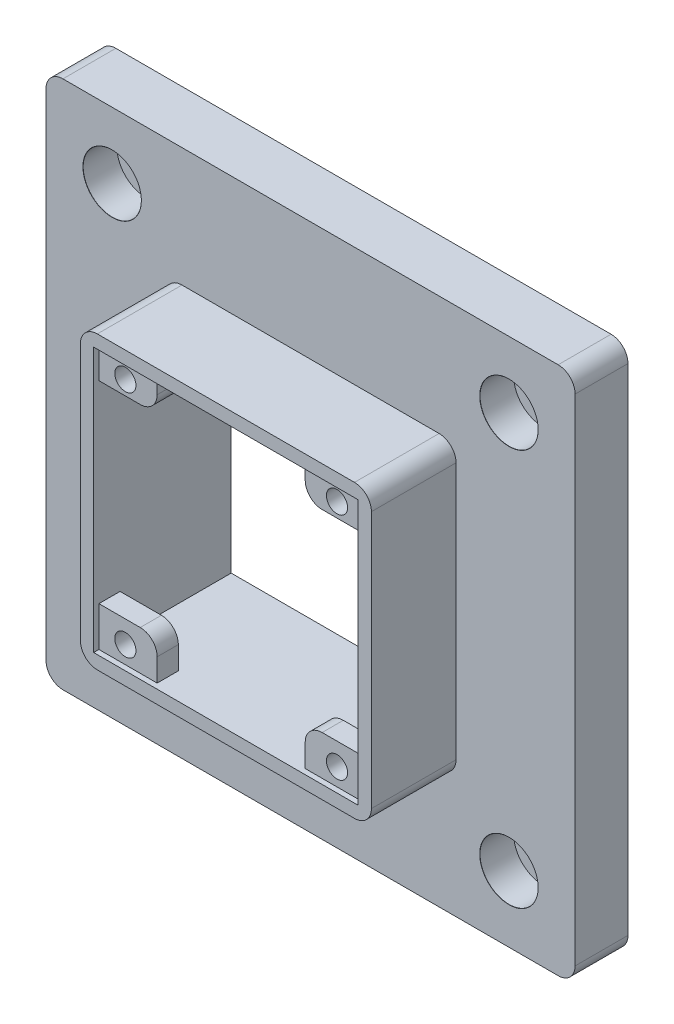
SolidWorks part; units mm, degrees
ref_plane "Front Plane" through (0, 0, 0) normal (1, 0, 0) x (0, 1, 0)
ref_plane "Top Plane" through (0, 0, 0) normal (0, 0, 1) x (0, 1, 0)
ref_plane "Right Plane" through (0, 0, 0) normal (0, 1, 0) x (-1, 0, 0)
sketch "Sketch2" plane through (0, 0, 0) normal (0, 0, 1) x (0, 1, 0)
  line L0 (25, 25) -> (50, 50)
  line L1 (-50, 50) -> (50, 50)
  line L2 (-50, 50) -> (-50, -50)
  line L3 (-50, -50) -> (50, -50)
  line L4 (50, 50) -> (50, -50)
  line L5 (-50, 50) -> (50, -50) construction
  line L6 (-50, -50) -> (50, 50) construction
  line L7 (-25, -25) -> (25, -25)
  line L8 (-25, -25) -> (-25, 25)
  line L9 (-25, 25) -> (25, 25)
  line L10 (25, -25) -> (25, 25)
  line L11 (-25, -25) -> (25, 25) construction
  line L12 (-25, 25) -> (25, -25) construction
  line L13 (25, -25) -> (50, -50)
  line L14 (37.5, 37.5) -> (37.5, -37.5)
  line L15 (37.5, -37.5) -> (37.5, -50)
  point P0 (0, 0)
  point P6 (0, 0)
  dimension "D1" = 50
  dimension "D2" = 100
extrude "Boss-Extrude1" add sketch "Sketch2" along normal blind 10 contours L7 L10 L9 L8 | L2 L1 L4 L3
sketch "Sketch5" plane through (0, 0, 10) normal (0, 0, 1) x (1, 0, 0)
  line L0 (-37.5, 37.5) -> (37.5, 37.5)
  line L2 (5.5, 0) -> (-5.5, 0) construction
  point P0 (-37.5, 37.5)
  point P1 (37.5, 37.5)
  point P13 (37.5, -37.5)
  point P14 (-37.5, -37.5)
hole_wizard "CBORE for M6 Hex Socket Head Cap Screw1" positions "Sketch5" profile "Sketch6" counterbore size "M6" standard "ISO" end condition through all
sketch "Sketch6" plane through (-37.5, 37.5, 10) normal (1, 0, 0) x (0, -1, 0)
  line L0 (0, 0) -> (0, 10)
  line L1 (0, 10) -> (3.3, 10)
  line L3 (3.3, 10) -> (3.3, 6.4)
  line L4 (5.5, 6.4) -> (3.3, 6.4)
  line L5 (5.5, 6.4) -> (5.5, 0.025)
  line L6 (5.5, 0.025) -> (5.525, 0)
  line L7 (5.525, 0) -> (0, 0)
  line L8 (-5.5, 0.025) -> (-5.525, 0) construction
  line L11 (0, -6.35) -> (0, 107.95) construction
  dimension "Thru Hole Dia." = 6.6
  dimension "Thru Hole Depth" = 10
  dimension "C'Bore Dia." = 11
  dimension "C'Bore Depth" = 6.4
  dimension "Near C'Sink Dia." = 11.05
  dimension "Near C'Sink Angle" = 90
sketch "Sketch7" plane through (0, 0, 10) normal (0, 0, 1) x (1, 0, 0)
  line L0 (25, 25) -> (50, 50) construction
  line L1 (-27.5, -27.5) -> (27.5, -27.5)
  line L2 (-27.5, -27.5) -> (-27.5, 27.5)
  line L3 (-27.5, 27.5) -> (27.5, 27.5)
  line L4 (27.5, -27.5) -> (27.5, 27.5)
  line L5 (-27.5, -27.5) -> (27.5, 27.5) construction
  line L6 (-27.5, 27.5) -> (27.5, -27.5) construction
  point P0 (0, 0)
  line M13 (25, 25) -> (25, -25)
  line M14 (25, -25) -> (-25, -25)
  line M15 (-25, -25) -> (-25, 25)
  line M16 (-25, 25) -> (25, 25)
  dimension "D1" = 55
extrude "Boss-Extrude2" add sketch "Sketch7" along normal blind 16 contours L1 L4 L3 L2 M16 M13 M14 M15
sketch "Sketch8" plane through (0, 0, 26) normal (0, 0, 1) x (1, 0, 0)
  line L0 (-50, -50) -> (50, 50) construction
  line L5 (-24.7015, -24.7015) -> (24.7015, 24.7015) construction
  line L7 (25, -25) -> (25, 25) construction
  line L8 (-25, 25) -> (25, 25)
  line L9 (-25, 25) -> (-25, 19)
  line L10 (-25, 19) -> (-13.9912, 19)
  line L11 (25, 25) -> (25, 19)
  line L12 (-13.9912, -17.5) -> (-25, -17.5)
  line L13 (-25, 25) -> (-13.9912, 25)
  line L14 (-25, -25) -> (25, -25)
  line L15 (-25, -25) -> (-25, -15)
  line L17 (25, -25) -> (25, -15)
  line L18 (-19.721, 19.721) -> (24.7015, -24.7015) construction
  line L19 (13.9912, 19) -> (25, 19)
  line L20 (-13.9912, -25) -> (-13.9912, -17.5)
  line L21 (13.9912, -25) -> (-13.9912, -25)
  line L22 (13.9912, -25) -> (13.9912, -17.5)
  line L24 (0, -25) -> (0, -24.7015)
  line L27 (13.9912, 19) -> (13.9912, 25)
  line L28 (13.9912, 25) -> (-13.9912, 25)
  line L29 (-13.9912, 19) -> (-13.9912, 25)
  line L30 (25, -17.5) -> (13.9912, -17.5)
  line L31 (-25, 25) -> (-25, 19)
  line L32 (-25, 19) -> (-13.9912, 19)
  line L33 (-13.9912, 25) -> (-13.9912, 19)
  line L34 (13.9912, 25) -> (25, 25)
  line L35 (13.9912, 25) -> (13.9912, 19)
  line L36 (13.9912, 19) -> (25, 19)
  line L37 (25, 25) -> (25, 19)
  line L38 (13.9912, -17.5) -> (25, -17.5)
  line L39 (13.9912, -17.5) -> (13.9912, -25)
  line L40 (13.9912, -25) -> (25, -25)
  line L41 (25, -17.5) -> (25, -25)
  line L42 (-25, -17.5) -> (-13.9912, -17.5)
  line L43 (-25, -17.5) -> (-25, -25)
  line L44 (-25, -25) -> (-13.9912, -25)
  line L45 (-13.9912, -17.5) -> (-13.9912, -25)
  circle A0 centre (-20, 21.7015) radius 2
  circle A1 centre (20, 21.7015) radius 2
  circle A2 centre (20, -21.7015) radius 2
  circle A3 centre (-20, -21.7015) radius 2
  point P0 (0, 0)
  line M10 (-25, 25) -> (25, 25)
  line M11 (25, 25) -> (25, -25)
  line M12 (25, -25) -> (-25, -25)
  line M13 (-25, -25) -> (-25, 25)
  dimension "D5" = 4
  dimension "D8" = 4
  dimension "D1" = 49.403
  dimension "D2" = 6
  dimension "D3" = 10
  dimension "D4" = 40
  dimension "D7" = 40
other "AlignGroup1"
extrude "Boss-Extrude3" add sketch "Sketch8" against normal blind 5 contours L10 L29 A0 M10 M13 | L27 L19 A1 M11 M10 | L17 L30 L22 A2 M12 | L14 L20 L12 A3 M13
sketch "Sketch9" plane through (0, 0, 26) normal (0, 0, 1) x (1, 0, 0)
  line L1 (-25, -17.5) -> (-13.9912, -17.5)
  line L2 (-25, -17.5) -> (-25, -25)
  line L3 (-25, -25) -> (-13.9912, -25)
  line L4 (-13.9912, -17.5) -> (-13.9912, -25)
  line L5 (13.9912, -17.5) -> (25, -17.5)
  line L6 (13.9912, -17.5) -> (13.9912, -25)
  line L7 (13.9912, -25) -> (25, -25)
  line L8 (25, -17.5) -> (25, -25)
  line L9 (13.9912, 25) -> (25, 25)
  line L10 (13.9912, 25) -> (13.9912, 19)
  line L11 (13.9912, 19) -> (25, 19)
  line L12 (25, 25) -> (25, 19)
  line L13 (-25, 25) -> (-13.9912, 25)
  line L14 (-25, 25) -> (-25, 19)
  line L15 (-25, 19) -> (-13.9912, 19)
  line L16 (-13.9912, 25) -> (-13.9912, 19)
  circle A0 centre (-20, -21.7015) radius 2
extrude "Cut-Extrude1" cut sketch "Sketch9" against normal blind 1
fillet "Fillet1" radius 3.2 12 edges at (13.9912, 19, 23) (-13.9912, 19, 23) (13.9912, -17.5, 23) (-13.9912, -17.5, 23) (-27.5, -27.5, 18) (-50, -50, 5) (27.5, -27.5, 18) (50, -50, 5) (50, 50, 5) (27.5, 27.5, 18) (-50, 50, 5) (-27.5, 27.5, 18)
sketch "Sketch10" plane through (0, 0, 25) normal (0, 0, 1) x (1, 0, 0)
  point P0 (-20, -21.7015)
  point P1 (-20, 21.7015)
  point P3 (20, 21.7015)
  point P5 (20, -21.7015)
